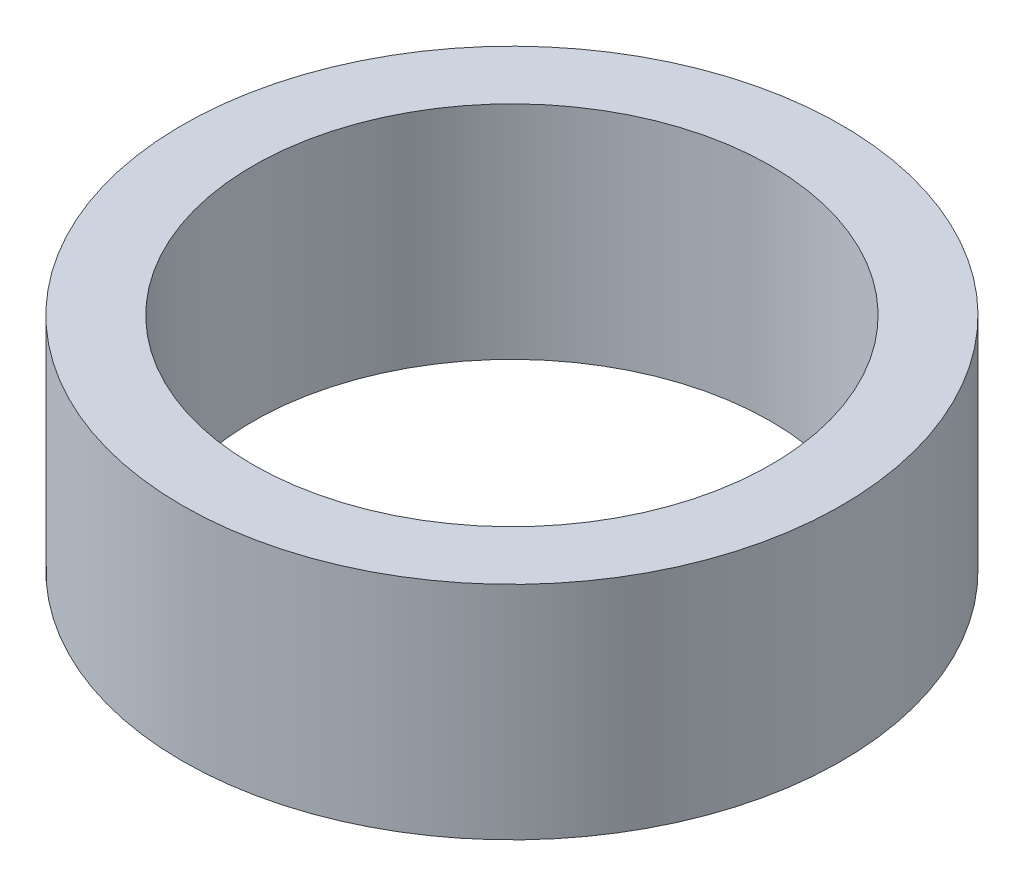
SolidWorks part; units mm, degrees
ref_plane "Plan de face" through (0, 0, 0) normal (0, 0, 1) x (1, 0, 0)
ref_plane "Plan de dessus" through (0, 0, 0) normal (0, 1, 0) x (1, 0, 0)
ref_plane "Plan de droite" through (0, 0, 0) normal (1, 0, 0) x (0, 0, -1)
sketch "Esquisse1" plane through (0, 0, 0) normal (0, 1, 0) x (1, 0, 0)
  circle A0 centre (0, 0) radius 3.5
  circle A1 centre (0, 0) radius 2.75
  dimension "D1" = 7
  dimension "D2" = 0.75
extrude "Boss.-Extru.1" add sketch "Esquisse1" along normal blind 2.35
